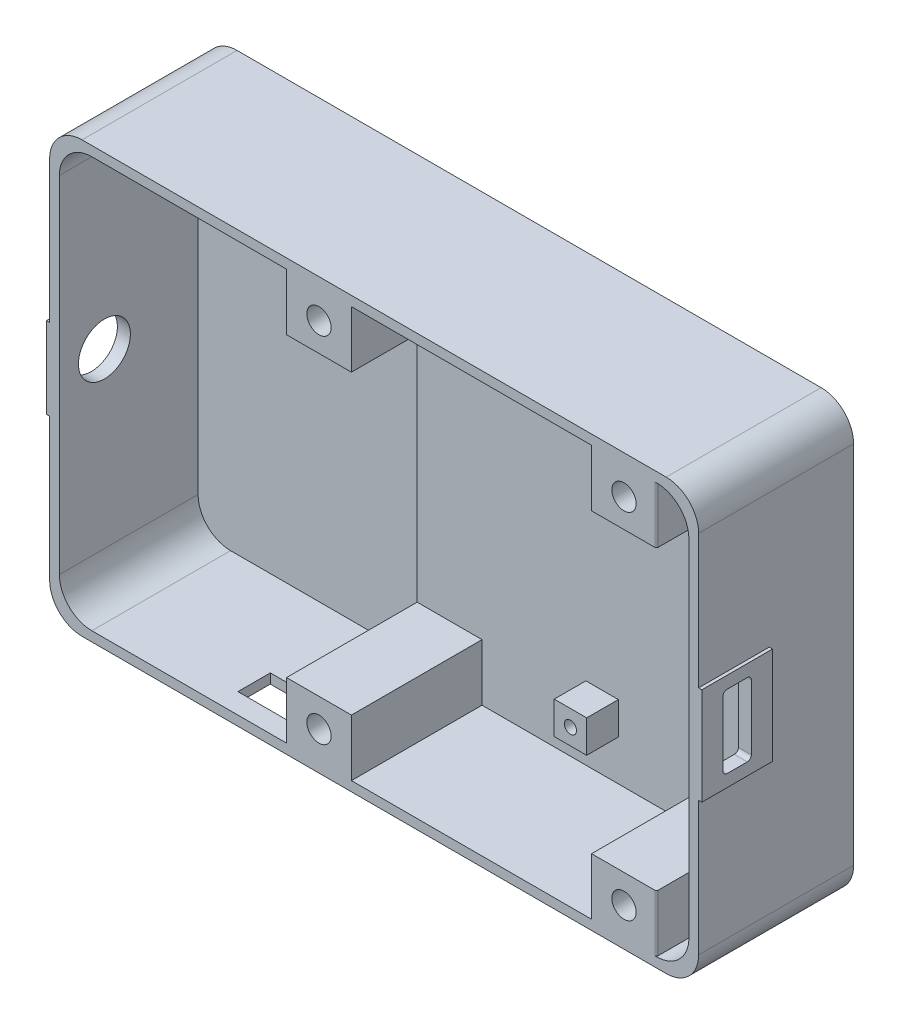
SolidWorks part; units mm, degrees
ref_plane "Plan de face" through (0, 0, 0) normal (0, 0, 1) x (1, 0, 0)
ref_plane "Plan de dessus" through (0, 0, 0) normal (0, 1, 0) x (1, 0, 0)
ref_plane "Plan de droite" through (0, 0, 0) normal (1, 0, 0) x (0, 0, -1)
sketch "Esquisse1" plane through (0, 0, 0) normal (0, 0, 1) x (1, 0, 0)
  line L1 (-40, -26.5) -> (40, -26.5)
  line L2 (-40, -26.5) -> (-40, 26.5)
  line L3 (-40, 26.5) -> (40, 26.5)
  line L4 (40, -26.5) -> (40, 26.5)
  line L5 (-40, -26.5) -> (40, 26.5) construction
  line L6 (-40, 26.5) -> (40, -26.5) construction
  point P0 (0, 0)
  dimension "D1" = 80
  dimension "D2" = 53
extrude "Boss.-Extru.1" add sketch "Esquisse1" along normal blind 19.1
sketch "Esquisse3" plane through (0, 0, 19.1) normal (0, 0, 1) x (1, 0, 0)
  line L1 (-38.8, -25.3) -> (38.8, -25.3)
  line L2 (-38.8, -25.3) -> (-38.8, 25.3)
  line L3 (-38.8, 25.3) -> (38.8, 25.3)
  line L4 (38.8, -25.3) -> (38.8, 25.3)
  line L5 (-38.8, -25.3) -> (38.8, 25.3) construction
  line L6 (-38.8, 25.3) -> (38.8, -25.3) construction
  point P0 (0, 0)
  dimension "D1" = 77.6
  dimension "D2" = 50.6
extrude "Enlèv. mat.-Extru.1" cut sketch "Esquisse3" against normal blind 16.1
fillet "Congé1" radius 4 8 edges at (-38.8, -25.3, 11.05) (38.8, -25.3, 11.05) (38.8, 25.3, 11.05) (-38.8, 25.3, 11.05) (40, -26.5, 9.55) (-40, -26.5, 9.55) (-40, 26.5, 9.55) (40, 26.5, 9.55)
sketch "Esquisse8" plane through (0, 0, 3) normal (0, 0, 1) x (1, 0, 0)
  line L0 (0, 0) -> (0, -25.3) construction
  line L1 (-34.8, -25.3) -> (34.8, -25.3) construction
  line L2 (0, -25.3) -> (-10.8, -25.3) construction
  dimension "D1" = 10.8
sketch "Esquisse9" plane through (0, 0, 3) normal (0, 0, 1) x (1, 0, 0)
  line L1 (-10.8, -25.3) -> (-2.8, -25.3)
  line L2 (-10.8, -25.3) -> (-10.8, -18.3)
  line L3 (-10.8, -18.3) -> (-2.8, -18.3)
  line L4 (-2.8, -25.3) -> (-2.8, -18.3)
  dimension "D1" = 8
  dimension "D2" = 7
extrude "Boss.-Extru.2" add sketch "Esquisse9" along normal up to surface (16.1 mm away) up to face at (0, 0, 19.1)
sketch "Esquisse10" plane through (0, 0, 19.1) normal (0, 0, 1) x (1, 0, 0)
  line L0 (-10.8, -18.3) -> (-2.8, -25.3) construction
sketch "Esquisse11" plane through (0, 0, 19.1) normal (0, 0, 1) x (1, 0, 0)
  line L0 (-10.8, -18.3) -> (-2.8, -25.3) construction
  circle A0 centre (-6.8, -21.8) radius 1.5
  dimension "D1" = 3
extrude "Enlèv. mat.-Extru.2" cut sketch "Esquisse11" against normal blind 13.1
mirror "Symétrie2" about plane through (0, 0, 0) normal (0, 1, 0) of "Enlèv. mat.-Extru.2", "Boss.-Extru.2"
sketch "Esquisse14" plane through (0, 0, 3) normal (0, 0, 1) x (1, 0, 0)
  line L1 (34.8, -25.3) -> (26.8, -25.3)
  line L2 (34.8, -25.3) -> (34.8, -18.3)
  line L3 (34.8, -18.3) -> (26.8, -18.3)
  line L4 (26.8, -25.3) -> (26.8, -18.3)
  dimension "D1" = 8
  dimension "D2" = 7
extrude "Boss.-Extru.3" add sketch "Esquisse14" along normal up to surface (16.1 mm away) up to face at (-5.3, 21.8, 19.1)
sketch "Esquisse15" plane through (0, 0, 19.1) normal (0, 0, 1) x (1, 0, 0)
  line L0 (26.8, -18.3) -> (34.8, -25.3) construction
  circle A0 centre (30.8, -21.8) radius 1.5
  dimension "D1" = 3
extrude "Enlèv. mat.-Extru.3" cut sketch "Esquisse15" against normal blind 13.1
mirror "Symétrie3" about plane through (0, 0, 0) normal (0, 1, 0) of "Enlèv. mat.-Extru.3", "Boss.-Extru.3"
sketch "Esquisse17" plane through (40, 0, 0) normal (1, 0, 0) x (0, 0, -1)
  line L0 (0, 0) -> (-14.75, 0) construction
  dimension "D1" = 14.75
sketch "Esquisse45" plane through (40, 0, 0) normal (1, 0, 0) x (0, 0, -1)
  line L0 (-19.1, -22.5) -> (-19.1, 22.5) construction
  line L1 (-10.4, -6) -> (-19.1, -6)
  line L2 (-10.4, -6) -> (-10.4, 6)
  line L3 (-10.4, 6) -> (-19.1, 6)
  line L4 (-19.1, -6) -> (-19.1, 6)
  line L5 (-10.4, -6) -> (-19.1, 6) construction
  line L6 (-10.4, 6) -> (-19.1, -6) construction
  point P0 (-14.75, 0)
  dimension "D1" = 12
extrude "Boss.-Extru.8" add sketch "Esquisse45" along normal blind 0.4
sketch "Esquisse18" plane through (40, 0, 0) normal (1, 0, 0) x (0, 0, -1)
  line L1 (-16.5, -4.5) -> (-13, -4.5)
  line L2 (-16.5, -4.5) -> (-16.5, 4.5)
  line L3 (-16.5, 4.5) -> (-13, 4.5)
  line L4 (-13, -4.5) -> (-13, 4.5)
  line L5 (-16.5, -4.5) -> (-13, 4.5) construction
  line L6 (-16.5, 4.5) -> (-13, -4.5) construction
  point P0 (-14.75, 0)
  dimension "D1" = 3.5
  dimension "D2" = 9
extrude "Enlèv. mat.-Extru.4" cut sketch "Esquisse18" against normal up to next and the other way through all
fillet "Congé2" radius 0.5 4 edges at (39.6, -4.5, 13) (39.6, -4.5, 16.5) (39.6, 4.5, 13) (39.6, 4.5, 16.5)
sketch "Esquisse31" plane through (0, 0, 3) normal (0, 0, 1) x (1, 0, 0)
  line L0 (-2.8, -18.3) -> (26.8, -18.3) construction
sketch "Esquisse33" plane through (0, 0, 3) normal (0, 0, 1) x (1, 0, 0)
  line L0 (-2.8, -18.3) -> (26.8, -18.3) construction
  line L1 (10, -20.3) -> (14, -20.3)
  line L2 (10, -20.3) -> (10, -16.3)
  line L3 (10, -16.3) -> (14, -16.3)
  line L4 (14, -20.3) -> (14, -16.3)
  line L5 (10, -20.3) -> (14, -16.3) construction
  line L6 (10, -16.3) -> (14, -20.3) construction
  point P0 (12, -18.3)
  dimension "D1" = 4
  dimension "D2" = 4
extrude "Boss.-Extru.6" add sketch "Esquisse33" along normal blind 3.9
sketch "Esquisse35" plane through (0, 0, 6.9) normal (0, 0, 1) x (1, 0, 0)
  line L0 (-2.8, -18.3) -> (26.8, -18.3) construction
  circle A0 centre (12, -18.3) radius 0.75
  dimension "D1" = 1.5
extrude "Enlèv. mat.-Extru.6" cut sketch "Esquisse35" against normal blind 2.9
mirror "Symétrie4" about plane through (0, 0, 0) normal (0, 1, 0) of "Boss.-Extru.6", "Enlèv. mat.-Extru.6"
sketch "Esquisse38" plane through (0, 0, 3) normal (0, 0, 1) x (1, 0, 0)
  line L0 (-10.8, -25.3) -> (-10.8, 25.3)
  line L1 (-10.8, 25.3) -> (-34.8, 25.3)
  line L2 (-38.8, 21.3) -> (-38.8, -21.3)
  line L3 (-34.8, -25.3) -> (-10.8, -25.3)
  arc A0 (-34.8, 25.3) -> (-38.8, 21.3) centre (-34.8, 21.3) ccw
  arc A1 (-38.8, -21.3) -> (-34.8, -25.3) centre (-34.8, -21.3) ccw
extrude "Enlèv. mat.-Extru.7" cut sketch "Esquisse38" against normal blind 1
fillet "Congé4" radius 0.5 1 edges at (-10.8, 0, 2)
sketch "Esquisse39" plane through (-40, 0, 0) normal (-1, 0, 0) x (0, 0, 1)
  line L0 (0, 0) -> (13.55, 0) construction
  dimension "D1" = 13.55
sketch "Esquisse40" plane through (-40, 0, 0) normal (-1, 0, 0) x (0, 0, 1)
  circle A0 centre (13.55, 0) radius 3.2
  dimension "D1" = 6.4
sketch "Esquisse42" plane through (-38.8, 0, 0) normal (1, 0, 0) x (0, 0, -1)
  line L0 (0, 0) -> (-13.55, 0) construction
  line L1 (-19.1, 21.3) -> (-19.1, -21.3) construction
  line L2 (-8, -5) -> (-19.1, -5)
  line L3 (-8, -5) -> (-8, 5)
  line L4 (-8, 5) -> (-19.1, 5)
  line L5 (-19.1, -5) -> (-19.1, 5)
  line L6 (-8, -5) -> (-19.1, 5) construction
  line L7 (-8, 5) -> (-19.1, -5) construction
  dimension "D1" = 13.55
  dimension "D2" = 10
  dimension "D3" = 11.1
extrude "Boss.-Extru.9" add sketch "Esquisse42" against normal blind 1.6
extrude "Enlèv. mat.-Extru.9" cut sketch "Esquisse40" against normal up to next and the other way through all
fillet "Congé5" radius 0.2 2 edges at (34.8, -21.8, 19.1) (34.8, 21.8, 19.1)
sketch "Esquisse50" plane through (0, 0, 19.1) normal (0, 0, 1) x (1, 0, 0)
  line L0 (-10.8, -25.3) -> (-10.8, -26.5) construction
  line L1 (-36, -26.5) -> (36, -26.5) construction
sketch "Esquisse52" plane through (0, -26.5, 0) normal (0, -1, 0) x (-1, 0, 0)
  line L0 (10.8, -19.1) -> (10.8, -16.6) construction
sketch "Esquisse53" plane through (0, -26.5, 0) normal (0, -1, 0) x (-1, 0, 0)
  line L1 (10.8, -16.6) -> (19.3, -16.6)
  line L2 (10.8, -16.6) -> (10.8, -12.6)
  line L3 (10.8, -12.6) -> (19.3, -12.6)
  line L4 (19.3, -16.6) -> (19.3, -12.6)
  dimension "D1" = 8.5
  dimension "D2" = 4
extrude "Enlèv. mat.-Extru.10" cut sketch "Esquisse53" against normal up to next
